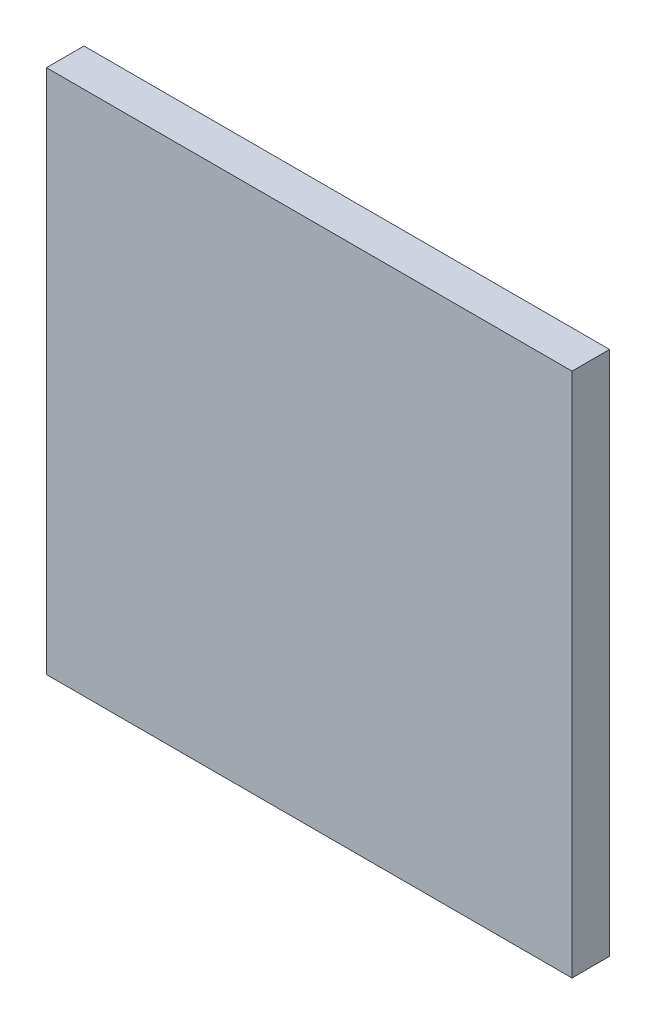
SolidWorks part; units mm, degrees
ref_plane "Front Plane" through (0, 0, 0) normal (0, 0, 1) x (1, 0, 0)
ref_plane "Top Plane" through (0, 0, 0) normal (0, 1, 0) x (1, 0, 0)
ref_plane "Right Plane" through (0, 0, 0) normal (1, 0, 0) x (0, 0, -1)
sketch "Sketch1" plane through (0, 0, 0) normal (0, 0, 1) x (1, 0, 0)
  line L1 (-70, -70) -> (70, -70)
  line L2 (-70, -70) -> (-70, 70)
  line L3 (-70, 70) -> (70, 70)
  line L4 (70, -70) -> (70, 70)
  line L5 (-70, -70) -> (70, 70) construction
  line L6 (-70, 70) -> (70, -70) construction
  point P0 (0, 0)
  dimension "D1" = 140
  dimension "D2" = 140
extrude "Boss-Extrude1" add sketch "Sketch1" along normal blind 10
sketch "Sketch2" plane through (0, 0, 0) normal (0, 0, 1) x (1, 0, 0)
  circle A0 centre (-31.9, 0) radius 5
  circle A1 centre (31.9, 0) radius 5
  dimension "D1" = 10
  dimension "D2" = 31.9
  dimension "D3" = 31.9
extrude "Boss-Extrude2" add sketch "Sketch2" against normal blind 30
